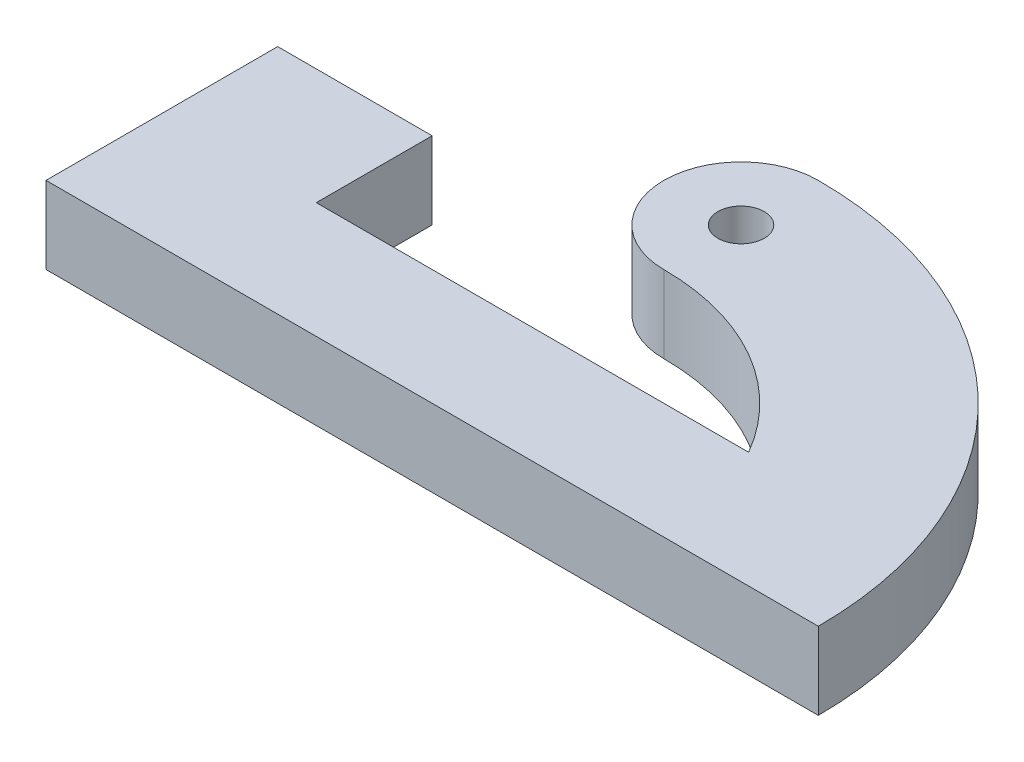
SolidWorks part; units mm, degrees
ref_plane "前视基准面" through (0, 0, 0) normal (0, 0, 1) x (1, 0, 0)
ref_plane "上视基准面" through (0, 0, 0) normal (0, 1, 0) x (1, 0, 0)
ref_plane "右视基准面" through (0, 0, 0) normal (1, 0, 0) x (0, 0, -1)
other "Configuration Table"
sketch "草图1" plane through (0, 0, 0) normal (0, 1, 0) x (1, 0, 0)
  line L2 (-50, 0) -> (0, 0)
  line L4 (-50, 0) -> (-50, 30)
  line L5 (-50, 30) -> (-30, 30)
  line L6 (-30, 15) -> (-30, 30)
  line L7 (0, 0) -> (50, 0)
  line L8 (-30, 15) -> (25.9808, 15)
  arc A0 (50, 0) -> (0, 50) centre (0, 0) ccw
  arc A1 (25.9808, 15) -> (0, 30) centre (0, 0) ccw
  arc A2 (0, 50) -> (0, 30) centre (0, 40) ccw
  circle A3 centre (0, 40) radius 3
  dimension "D1" = 30
  dimension "D2" = 50
  dimension "D5" = 6
  dimension "D3" = 20
  dimension "D4" = 30
extrude "凸台-拉伸1" add sketch "草图1" along normal blind 10
